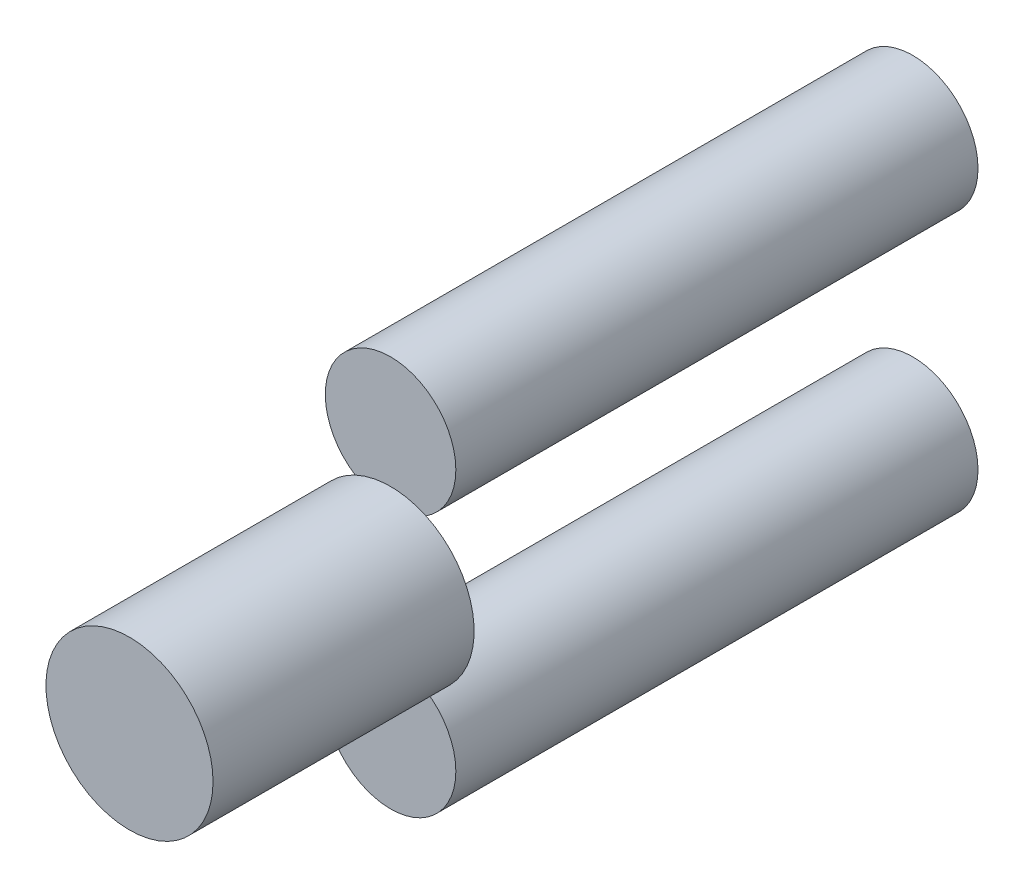
SolidWorks part; units mm, degrees
ref_plane "Front Plane" through (0, 0, 0) normal (0, 0, 1) x (1, 0, 0)
ref_plane "Top Plane" through (0, 0, 0) normal (0, 1, 0) x (1, 0, 0)
ref_plane "Right Plane" through (0, 0, 0) normal (1, 0, 0) x (0, 0, -1)
sketch "Sketch1" plane through (0, 0, 0) normal (0, 0, 1) x (1, 0, 0)
  line L0 (0, 0) -> (0, 19.05) construction
  circle A0 centre (0, 12.7) radius 1.5875
  circle A1 centre (0, 19.05) radius 1.5875
  dimension "D2" = 3.175
  dimension "D1" = 6.35
  dimension "D3" = 12.7
extrude "Boss-Extrude1" add sketch "Sketch1" against normal blind 12.7
sketch "Sketch2" plane through (0, 0, 0) normal (0, 0, 1) x (1, 0, 0)
  line L0 (0, 17.4625) -> (0, 14.2875) construction
  circle A0 centre (0, 15.875) radius 2.032
  circle A1 centre (0, 19.05) radius 1.5875 construction
  circle A2 centre (0, 12.7) radius 1.5875 construction
  dimension "D1" = 4.064
extrude "Boss-Extrude2" add sketch "Sketch2" along normal blind 6.35
equation "\"D1@Sketch1\"=2*0.125"
